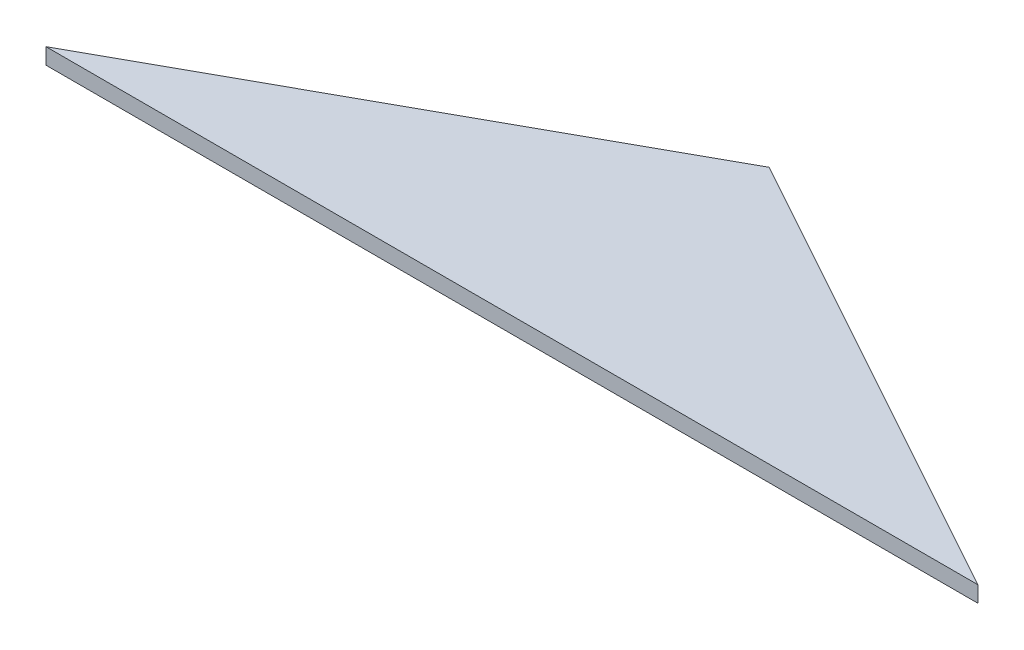
SolidWorks part; units mm, degrees
ref_plane "Alzado" through (0, 0, 0) normal (0, 0, 1) x (1, 0, 0)
ref_plane "Planta" through (0, 0, 0) normal (0, 1, 0) x (1, 0, 0)
ref_plane "Vista lateral" through (0, 0, 0) normal (1, 0, 0) x (0, 0, -1)
sketch "Sketch1" plane through (0, 0, 0) normal (0, 1, 0) x (1, 0, 0)
  line L0 (-145, 0) -> (145, 0)
  line L1 (0, 0) -> (0, 80) construction
  line L2 (-145, 0) -> (0, 80)
  line L3 (0, 80) -> (145, 0)
  point P2 (0, 0)
  point P7 (0, 0)
  dimension "D1" = 290
extrude "Boss-Extrude1" add sketch "Sketch1" along normal blind 5
